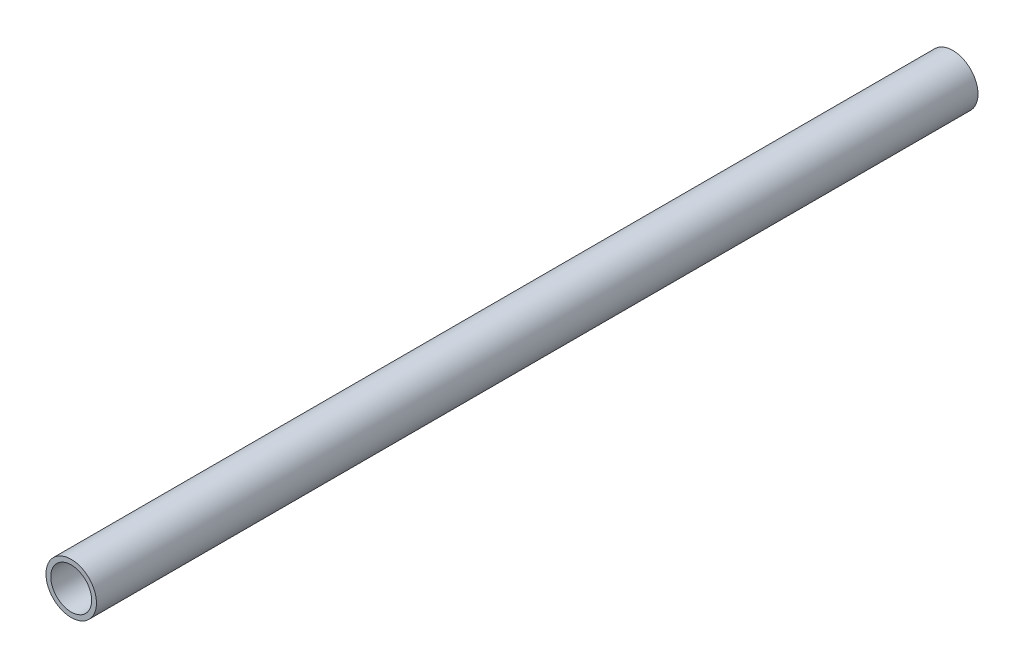
SolidWorks part; units mm, degrees
ref_plane "Front Plane" through (0, 0, 0) normal (0, 0, 1) x (1, 0, 0)
ref_plane "Top Plane" through (0, 0, 0) normal (0, 1, 0) x (1, 0, 0)
ref_plane "Right Plane" through (0, 0, 0) normal (1, 0, 0) x (0, 0, -1)
sketch "Sketch1" plane through (0, 0, 0) normal (0, 0, 1) x (1, 0, 0)
  circle A0 centre (0, 0) radius 6.477
  circle A1 centre (0, 0) radius 8.001
  dimension "D1" = 16.002
  dimension "D2" = 1.524
extrude "Boss-Extrude1" add sketch "Sketch1" against normal blind 279.4
equation "\"Pushrod_length\"= 11"
equation "\"Pushrod_outer_diameter\"= .63"
equation "\"Pushrod_thickness\" = .06"
equation "\"D1@Sketch1\"=\"Pushrod_outer_diameter\""
equation "\"D2@Sketch1\"=\"Pushrod_thickness\""
equation "\"D1@Boss-Extrude1\"=\"Pushrod_length\""
